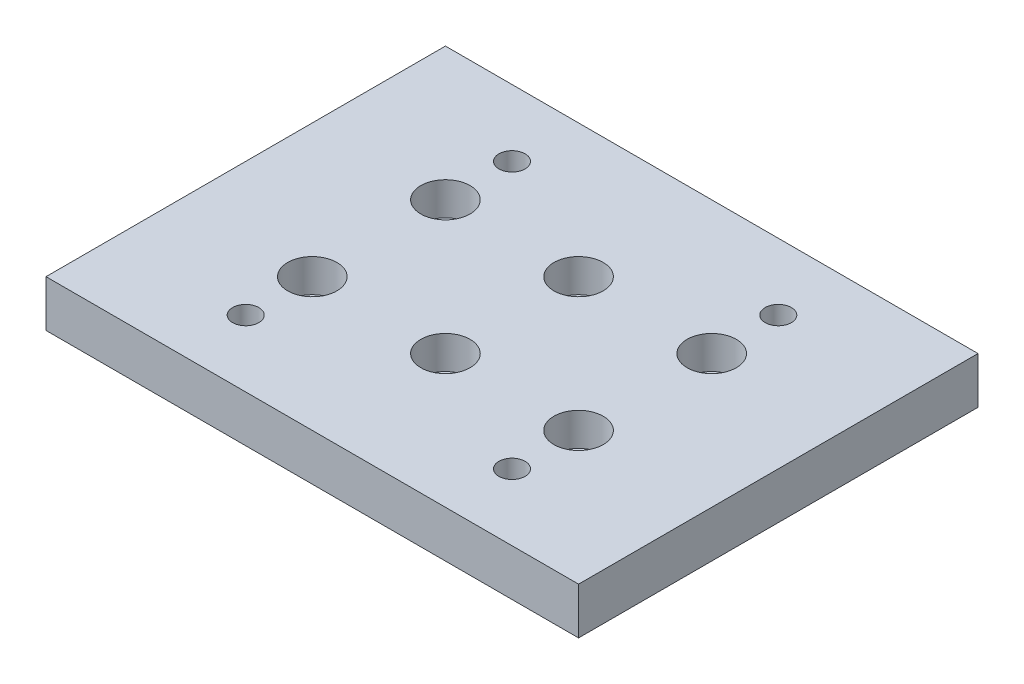
SolidWorks part; units mm, degrees
ref_plane "Front Plane" through (0, 0, 0) normal (0, 0, 1) x (1, 0, 0)
ref_plane "Top Plane" through (0, 0, 0) normal (0, 1, 0) x (1, 0, 0)
ref_plane "Right Plane" through (0, 0, 0) normal (1, 0, 0) x (0, 0, -1)
sketch "Sketch1" plane through (0, 0, 0) normal (0, 1, 0) x (1, 0, 0)
  line L1 (-50.8, 38.1) -> (50.8, 38.1)
  line L2 (-50.8, 38.1) -> (-50.8, -38.1)
  line L3 (-50.8, -38.1) -> (50.8, -38.1)
  line L4 (50.8, 38.1) -> (50.8, -38.1)
  point P4 (0, 38.1)
  point P5 (50.8, 0)
  dimension "D1" = 101.6
  dimension "D2" = 76.2
  dimension "D3" = 38.1
  dimension "D4" = 50.8
extrude "Boss-Extrude1" add sketch "Sketch1" along normal blind 8.89
hole_wizard "Tap Drill for M6x1.0 Tap1" positions "Sketch3" profile "Sketch4" hole size "M6x1.0" standard "ANSI Metric" end condition through all
sketch "Sketch3" plane through (0, 8.89, 0) normal (0, 1, 0) x (1, 0, 0)
  line L0 (-50.8, 38.1) -> (-50.8, -38.1) construction
  line L1 (50.8, 38.1) -> (-50.8, 38.1) construction
  line L2 (-50.8, -38.1) -> (50.8, -38.1) construction
  line L3 (50.8, -38.1) -> (50.8, 38.1) construction
  point P0 (-25.4, 25.4)
  point P2 (25.4, 25.4)
  point P4 (25.4, -25.4)
  point P6 (-25.4, -25.4)
  dimension "D1" = 50.8
  dimension "D2" = 50.8
  dimension "D3" = 50.8
  dimension "D4" = 50.8
  dimension "D5" = 25.4
  dimension "D6" = 12.7
  dimension "D7" = 12.7
  dimension "D8" = 25.4
sketch "Sketch4" plane through (-25.4, 8.89, -25.4) normal (1, 0, 0) x (0, 0, 1)
  line L0 (0, 0) -> (0, 8.89)
  line L1 (0, 8.89) -> (2.5, 8.89)
  line L2 (2.5, 8.89) -> (2.5, 0)
  line L5 (2.5, 0) -> (0, 0)
  line L11 (0, -6.35) -> (0, 107.95) construction
  dimension "Thru Hole Dia." = 5
  dimension "Thru Hole Depth" = 8.89
hole_wizard "CBORE for M6 SHCS1" positions "Sketch7" profile "Sketch8" counterbore size "M6" standard "ANSI Metric" end condition through all
sketch "Sketch7" plane through (0, 8.89, 0) normal (0, 1, 0) x (1, 0, 0)
  line L0 (50.8, 38.1) -> (-50.8, 38.1) construction
  line L1 (-50.8, 38.1) -> (-50.8, -38.1) construction
  line L3 (50.8, -38.1) -> (50.8, 38.1) construction
  point P0 (-25.4, 12.7)
  point P2 (-25.4, -12.7)
  point P4 (0, -12.7)
  point P6 (0, 12.7)
  point P8 (25.4, 12.7)
  point P10 (25.4, -12.7)
  point P13 (0, 0)
  point P14 (0, 0)
  dimension "D1" = 25.4
  dimension "D2" = 25.4
  dimension "D3" = 25.4
  dimension "D4" = 25.4
  dimension "D5" = 25.4
  dimension "D6" = 25.4
  dimension "D7" = 25.4
  dimension "D8" = 25.4
  dimension "D9" = 25.4
  dimension "D10" = 25.4
  dimension "D11" = 25.4
  dimension "D12" = 25.4
sketch "Sketch8" plane through (-25.4, 8.89, -12.7) normal (1, 0, 0) x (0, 0, 1)
  line L0 (0, 0) -> (0, 8.89)
  line L1 (0, 8.89) -> (3.3, 8.89)
  line L3 (3.3, 8.89) -> (3.3, 6.3)
  line L4 (3.3, 6.3) -> (4.7, 6.3)
  line L5 (4.7, 6.3) -> (4.7, 0)
  line L7 (4.7, 0) -> (0, 0)
  line L11 (0, -6.35) -> (0, 107.95) construction
  dimension "Thru Hole Dia." = 6.6
  dimension "Thru Hole Depth" = 8.89
  dimension "C'Bore Dia." = 9.4
  dimension "C'Bore Depth" = 6.3
